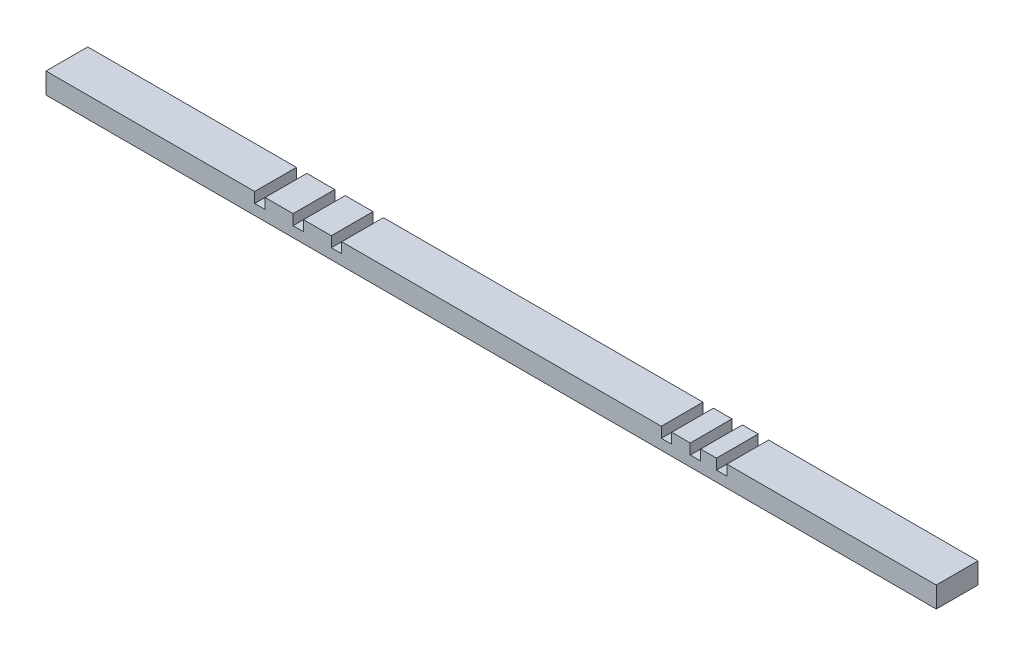
SolidWorks part; units mm, degrees
material "Pine"
ref_plane "Front Plane" through (0, 0, 0) normal (0, 0, 1) x (1, 0, 0)
ref_plane "Top Plane" through (0, 0, 0) normal (0, 1, 0) x (1, 0, 0)
ref_plane "Right Plane" through (0, 0, 0) normal (1, 0, 0) x (0, 0, -1)
sketch "Sketch1" plane through (0, 0, 0) normal (0, 1, 0) x (1, 0, 0)
  line L1 (0, 0) -> (812.8, 0)
  line L2 (0, 0) -> (0, -38.1)
  line L3 (0, -38.1) -> (812.8, -38.1)
  line L4 (812.8, 0) -> (812.8, -38.1)
  dimension "D1" = 812.8
  dimension "D2" = 38.1
extrude "Boss-Extrude1" add sketch "Sketch1" along normal blind 19.05
sketch "Sketch2" plane through (0, 19.05, 0) normal (0, 1, 0) x (1, 0, 0)
  line L4 (812.8, 0) -> (0, 0) construction
  line L6 (621.6493, -19.05) -> (621.6493, 0)
  line L7 (621.6493, 0) -> (612.1243, 0)
  line L8 (612.1243, -19.05) -> (612.1243, 0)
  line L9 (0, -38.1) -> (812.8, -38.1) construction
  line L11 (612.1243, -19.05) -> (612.1243, -38.1)
  line L12 (612.1243, -38.1) -> (621.6493, -38.1)
  line L13 (621.6493, -19.05) -> (621.6493, -38.1)
  line L16 (597.7131, -19.05) -> (597.7131, 0)
  line L17 (597.7131, 0) -> (588.1881, 0)
  line L18 (588.1881, -19.05) -> (588.1881, 0)
  line L20 (597.7131, -19.05) -> (597.7131, -38.1)
  line L21 (597.7131, -38.1) -> (588.1881, -38.1)
  line L22 (588.1881, -19.05) -> (588.1881, -38.1)
  line L24 (571.2675, -19.05) -> (571.2675, 0)
  line L25 (571.2675, 0) -> (561.7425, 0)
  line L26 (561.7425, -19.05) -> (561.7425, 0)
  line L28 (571.2675, -19.05) -> (571.2675, -38.1)
  line L29 (571.2675, -38.1) -> (561.7425, -38.1)
  line L30 (561.7425, -19.05) -> (561.7425, -38.1)
  line L36 (190.5, -19.05) -> (190.5, 0)
  line L37 (190.5, 0) -> (200.025, 0)
  line L38 (200.025, -19.05) -> (200.025, 0)
  line L39 (225.5405, -19.05) -> (225.5405, 0)
  line L40 (225.5405, 0) -> (235.0655, 0)
  line L41 (200.025, -19.05) -> (200.025, -38.1)
  line L42 (200.025, -38.1) -> (190.5, -38.1)
  line L43 (190.5, -38.1) -> (190.5, -19.05)
  line L44 (235.0655, 0) -> (235.0655, -38.1)
  line L45 (235.0655, -38.1) -> (225.5405, -38.1)
  line L46 (225.5405, -38.1) -> (225.5405, -19.05)
  line L48 (260.4667, -19.05) -> (260.4667, 0)
  line L49 (260.4667, 0) -> (269.9917, 0)
  line L50 (269.9917, 0) -> (269.9917, -38.1)
  line L51 (269.9917, -38.1) -> (260.4667, -38.1)
  line L52 (260.4667, -38.1) -> (260.4667, -19.05)
  point P28 (0, 0)
  dimension "D1" = 9.525
  dimension "D2" = 9.525
  dimension "D3" = 9.525
  dimension "D5" = 9.525
  dimension "D6" = 9.525
  dimension "D7" = 9.525
extrude "Cut-Extrude3" cut sketch "Sketch2" against normal blind 9.525
